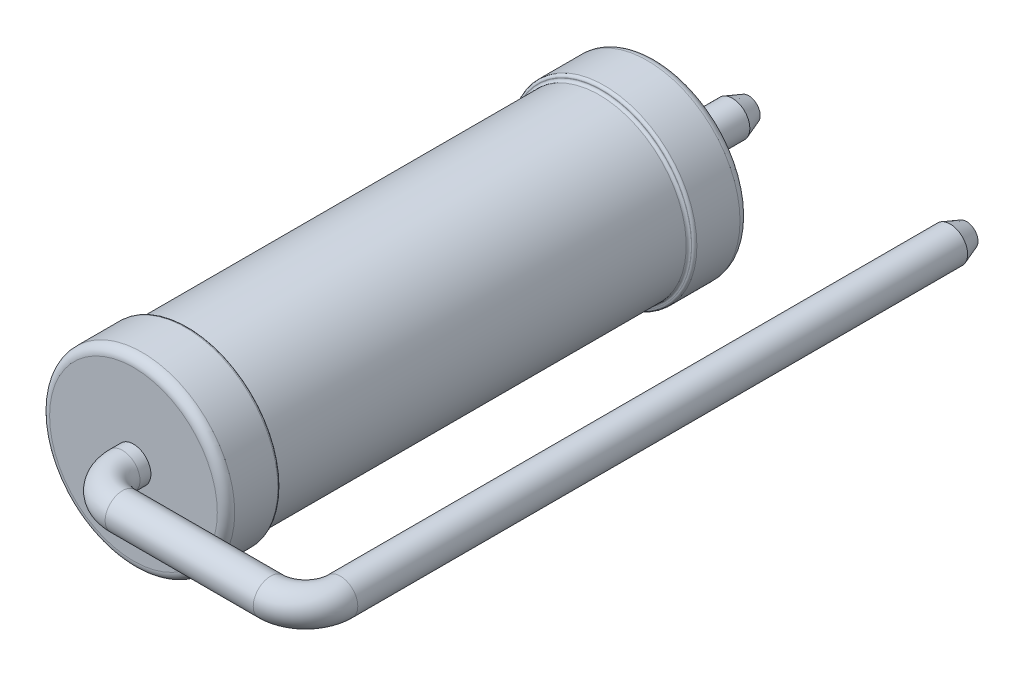
SolidWorks part; units mm, degrees
ref_plane "Front Plane" through (0, 0, 0) normal (0, 0, 1) x (1, 0, 0)
ref_plane "Top Plane" through (0, 0, 0) normal (0, 1, 0) x (1, 0, 0)
ref_plane "Right Plane" through (0, 0, 0) normal (1, 0, 0) x (0, 0, -1)
sketch "Sketch1" plane through (0, 0, 0) normal (0, 1, 0) x (1, 0, 0)
  line L0 (-2.54, -0.254) -> (2.54, -0.254) construction
  line L1 (-2.54, -0.254) -> (-2.54, -12.446) construction
  line L2 (-2.54, -12.446) -> (-4.4958, -12.446)
  line L3 (-4.699, -12.2428) -> (-4.699, -11.237)
  line L4 (-4.638, -11.176) -> (-4.633, -11.176)
  line L5 (-4.572, -11.115) -> (-4.572, -1.585)
  line L6 (-4.633, -1.524) -> (-4.638, -1.524)
  line L7 (-4.699, -1.463) -> (-4.699, -0.4572)
  line L8 (-4.4958, -0.254) -> (-2.54, -0.254)
  line L9 (-4.572, -6.35) -> (-2.54, -6.35) construction
  line L10 (-2.54, -0.254) -> (-2.54, -12.446)
  line L11 (0, 0) -> (0, -0.254) construction
  arc A0 (-4.699, -0.4572) -> (-4.4958, -0.254) centre (-4.4958, -0.4572) cw
  arc A1 (-4.4958, -12.446) -> (-4.699, -12.2428) centre (-4.4958, -12.2428) cw
  arc A2 (-4.638, -1.524) -> (-4.699, -1.463) centre (-4.638, -1.463) cw
  arc A3 (-4.572, -1.585) -> (-4.633, -1.524) centre (-4.633, -1.585) ccw
  arc A4 (-4.633, -11.176) -> (-4.572, -11.115) centre (-4.633, -11.115) ccw
  arc A5 (-4.699, -11.237) -> (-4.638, -11.176) centre (-4.638, -11.237) cw
  dimension "D2" = 0.2032
  dimension "EdgeRadius" = 0.2032
  dimension "D3" = 0.061
  dimension "D4" = 0.061
  dimension "D5" = 0.061
  dimension "D6" = 0.061
  dimension "D1" = 0.254
  dimension "Radius" = 2.159
  dimension "Radius2" = 2.032
  dimension "BodyLength" = 12.192
  dimension "BodyLength2" = 9.652
  dimension "Grid" = 5.08
revolve "Revolve1" add sketch "Sketch1" angle 360 about L10
ref_plane "Plane1" through (0, 0, -1.905) normal (0, 0, 1) x (1, 0, 0)
sketch "Sketch2" plane through (0, 0, 0) normal (0, 1, 0) x (1, 0, 0)
  line L0 (2.54, 1.905) -> (2.54, -12.7)
  line L1 (-1.2573, 1.905) -> (1.2573, 1.905) construction
  line L2 (1.7272, -13.5128) -> (-1.7272, -13.5128)
  line L3 (-2.54, -12.7) -> (-2.54, 1.905)
  line L4 (-2.54, 0) -> (2.54, 0) construction
  arc A0 (2.54, -12.7) -> (1.7272, -13.5128) centre (1.7272, -12.7) cw
  arc A1 (-1.7272, -13.5128) -> (-2.54, -12.7) centre (-1.7272, -12.7) cw
  dimension "PinEdgeRadius" = 0.8128
  dimension "D2" = 0.8128
  dimension "D3" = 13.5128
  dimension "D1" = 5.08
sketch "Sketch3" plane through (0, 0, -1.905) normal (0, 0, 1) x (1, 0, 0)
  circle A0 centre (2.54, 0) radius 0.4064
  dimension "PinDiameter" = 0.8128
sweep "Sweep1" add profiles "Sketch3" path "Sketch2"
chamfer "Chamfer1" distance 0.381 angle 20 2 edges at (-2.9464, 0, -1.905) (2.9464, 0, -1.905)
equation "\"D2@Sketch1\"=\"EdgeRadius@Sketch1\""
equation "\"D4@Sketch1\"=\"D3@Sketch1\""
equation "\"D6@Sketch1\"=\"D3@Sketch1\""
equation "\"D5@Sketch1\"=\"D3@Sketch1\""
equation "\"D3@Sketch1\"=(\"Radius@Sketch1\"-\"Radius2@Sketch1\")/2-0.1"
equation "\"D2@Sketch2\"=\"PinEdgeRadius@Sketch2\""
equation "\"D3@Sketch2\"=\"BodyLength@Sketch1\"+20+\"PinEdgeRadius@Sketch2\""
equation "\"D1@Sketch2\"=\"Grid@Sketch1\""
